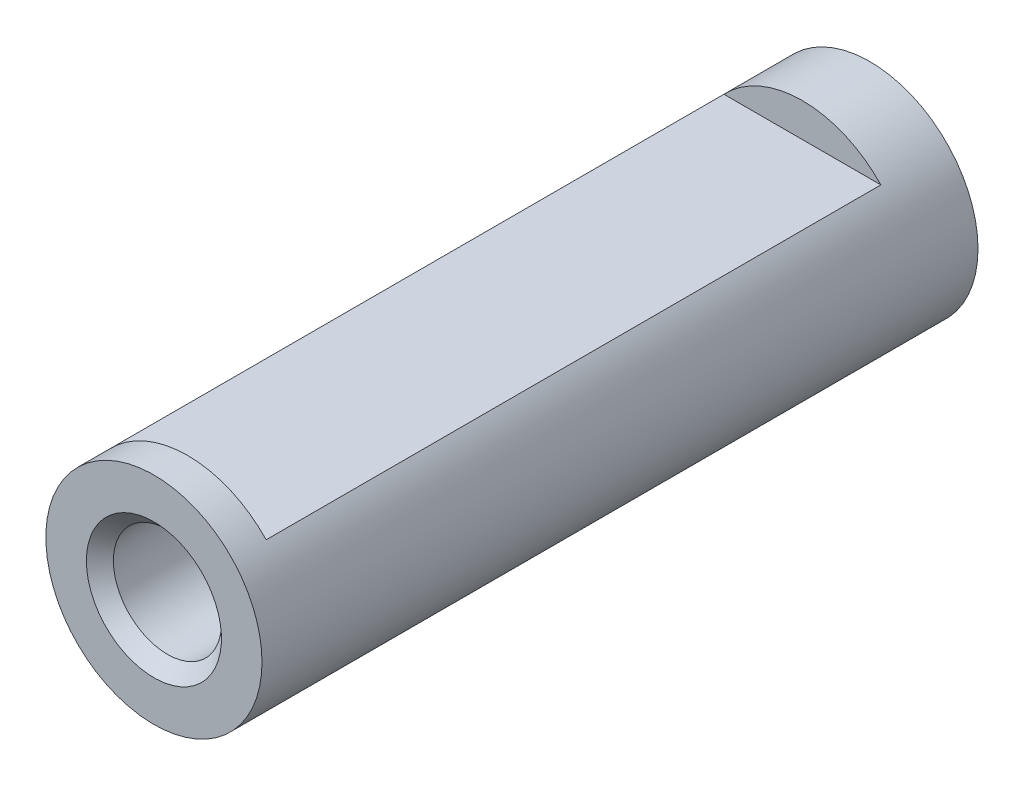
SolidWorks part; units mm, degrees
ref_plane "Front Plane" through (0, 0, 0) normal (0, 0, 1) x (1, 0, 0)
ref_plane "Top Plane" through (0, 0, 0) normal (0, 1, 0) x (1, 0, 0)
ref_plane "Right Plane" through (0, 0, 0) normal (1, 0, 0) x (0, 0, -1)
sketch "Croquis1" plane through (0, 0, 0) normal (1, 0, 0) x (0, 0, -1)
  line L0 (-35.8992, 0) -> (35.8992, 0) construction
  line L1 (-26.5, 4) -> (-26.5, 8)
  line L2 (-26.5, 8) -> (26.5, 8)
  line L3 (26.5, 8) -> (26.5, 4)
  line L4 (26.5, 4) -> (-26.5, 4)
  line L5 (0, 20.057) -> (0, -15.0959) construction
  dimension "D1" = 16
  dimension "D2" = 8
  dimension "D3" = 53
revolve "Revolución1" add sketch "Croquis1" angle 360 about L0
chamfer "Chaflán1" distance 1 angle 45 1 edges at (4, 0, 26.5)
sketch "Croquis2" plane through (0, 0, 0) normal (1, 0, 0) x (0, 0, -1)
  line L0 (-24, 5.5) -> (21.5, 5.5)
  line L1 (21.5, 5.5) -> (21.5, 8)
  line L2 (26.5, 8) -> (-26.5, 8) construction
  line L3 (21.5, 8) -> (-24, 8)
  line L4 (-24, 8) -> (-24, 5.5)
  line L5 (-26.5, 8) -> (-26.5, -8) construction
  line L6 (26.5, -8) -> (26.5, 8) construction
  dimension "D1" = 2.5
  dimension "D2" = 5
  dimension "D3" = 2.5
extrude "Cortar-Extruir1" cut sketch "Croquis2" against normal through all both and the other way through all
